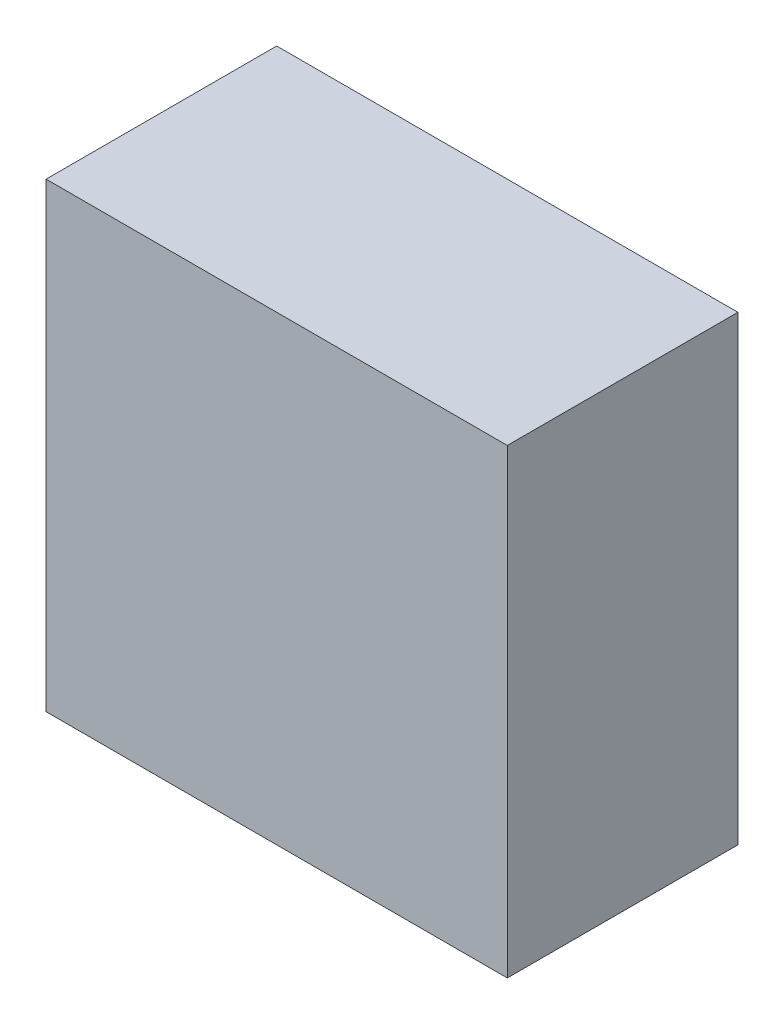
SolidWorks part; units mm, degrees
ref_plane "Front Plane" through (0, 0, 0) normal (0, 0, 1) x (1, 0, 0)
ref_plane "Top Plane" through (0, 0, 0) normal (0, 1, 0) x (1, 0, 0)
ref_plane "Right Plane" through (0, 0, 0) normal (1, 0, 0) x (0, 0, -1)
sketch "Sketch1" plane through (0, 0, 0) normal (0, 0, 1) x (1, 0, 0)
  line L1 (0, 0) -> (-200, 0)
  line L2 (0, 0) -> (0, 200)
  line L3 (0, 200) -> (-200, 200)
  line L4 (-200, 0) -> (-200, 200)
  dimension "D1" = 200
  dimension "D2" = 200
extrude "Boss-Extrude1" add sketch "Sketch1" along normal blind 100
